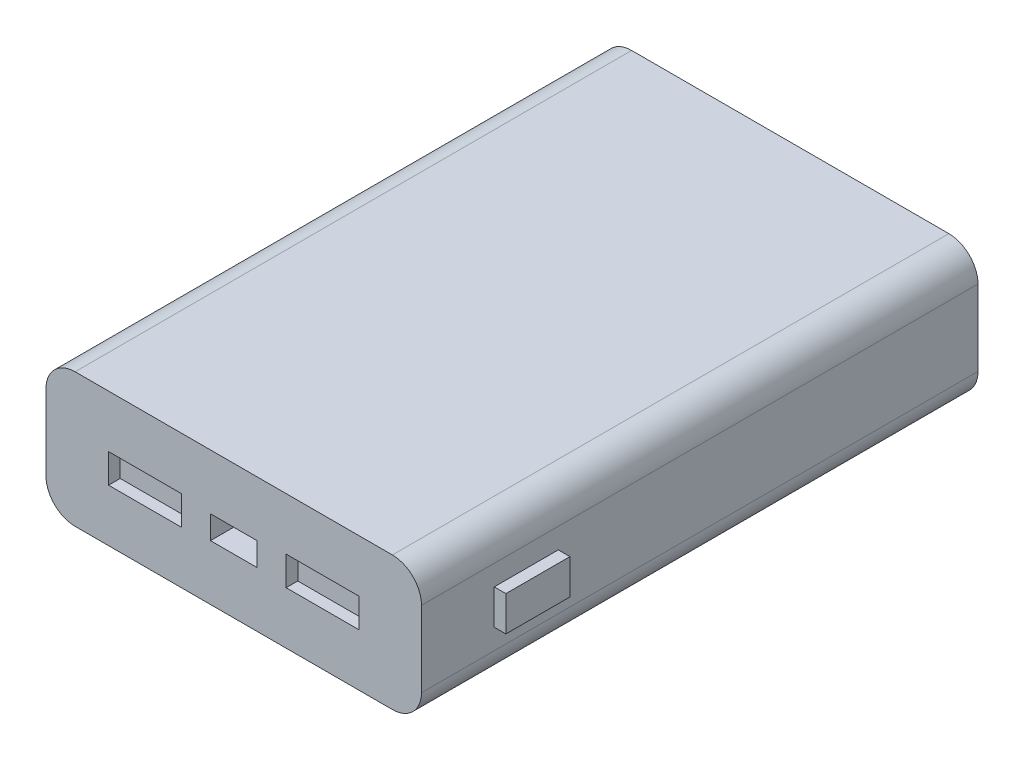
SolidWorks part; units mm, degrees
ref_plane "Front Plane" through (0, 0, 0) normal (0, 0, 1) x (1, 0, 0)
ref_plane "Top Plane" through (0, 0, 0) normal (0, 1, 0) x (1, 0, 0)
ref_plane "Right Plane" through (0, 0, 0) normal (1, 0, 0) x (0, 0, -1)
sketch "Sketch1" plane through (0, 0, 0) normal (0, 0, 1) x (1, 0, 0)
  line L1 (-32.25, -11.5) -> (32.25, -11.5)
  line L2 (-32.25, -11.5) -> (-32.25, 11.5)
  line L3 (-32.25, 11.5) -> (32.25, 11.5)
  line L4 (32.25, -11.5) -> (32.25, 11.5)
  line L5 (-32.25, -11.5) -> (32.25, 11.5) construction
  line L6 (-32.25, 11.5) -> (32.25, -11.5) construction
  point P0 (0, 0)
extrude "Boss-Extrude1" add sketch "Sketch1" along normal blind 95.6
fillet "Fillet1" radius 5 4 edges at (-32.25, -11.5, 47.8) (-32.25, 11.5, 47.8) (32.25, -11.5, 47.8) (32.25, 11.5, 47.8)
sketch "Sketch2" plane through (0, 0, 95.6) normal (0, 0, 1) x (1, 0, 0)
  line L1 (-4, -2) -> (4, -2)
  line L2 (-4, -2) -> (-4, 2)
  line L3 (-4, 2) -> (4, 2)
  line L4 (4, -2) -> (4, 2)
  line L5 (-4, -2) -> (4, 2) construction
  line L6 (-4, 2) -> (4, -2) construction
  point P0 (0, 0)
extrude "Cut-Extrude1" cut sketch "Sketch2" against normal blind 5
sketch "Sketch3" plane through (32.25, 0, 0) normal (1, 0, 0) x (0, 0, -1)
  line L0 (-95.6, 0) -> (-77.6, 0) construction
  line L5 (-95.6, -6.5) -> (-95.6, 6.5) construction
  line L7 (-83.1, -3) -> (-72.1, -3)
  line L8 (-83.1, -3) -> (-83.1, 3)
  line L9 (-83.1, 3) -> (-72.1, 3)
  line L10 (-72.1, -3) -> (-72.1, 3)
  line L11 (-83.1, -3) -> (-72.1, 3) construction
  line L12 (-83.1, 3) -> (-72.1, -3) construction
extrude "Boss-Extrude2" add sketch "Sketch3" along normal blind 2 separate body
sketch "Sketch4" plane through (0, 0, 95.6) normal (0, 0, 1) x (1, 0, 0)
  line L0 (-4, 2) -> (-4, -2) construction
  line L1 (-21.5, -2.5) -> (-9, -2.5)
  line L2 (-21.5, -2.5) -> (-21.5, 2.5)
  line L3 (-21.5, 2.5) -> (-9, 2.5)
  line L4 (-9, -2.5) -> (-9, 2.5)
  line L5 (-21.5, -2.5) -> (-9, 2.5) construction
  line L6 (-21.5, 2.5) -> (-9, -2.5) construction
  line L11 (0, 0) -> (0, 6.3343) construction
  line L12 (21.5, 2.5) -> (9, -2.5) construction
  line L13 (21.5, -2.5) -> (9, 2.5) construction
  line L14 (9, -2.5) -> (9, 2.5)
  line L15 (21.5, 2.5) -> (9, 2.5)
  line L16 (21.5, -2.5) -> (21.5, 2.5)
  line L17 (21.5, -2.5) -> (9, -2.5)
  point P0 (-15.25, 0)
  point P14 (15.25, 0)
  dimension "D1" = 5
extrude "Cut-Extrude2" cut sketch "Sketch4" against normal blind 2
sketch "Sketch5" plane through (0, -11.5, 0) normal (0, -1, 0) x (1, 0, 0)
  line L0 (-27.25, 95.6) -> (27.25, 95.6) construction
  line L1 (7.75, 73.1) -> (24.75, 73.1)
  line L2 (7.75, 73.1) -> (7.75, 86.1)
  line L3 (7.75, 86.1) -> (24.75, 86.1)
  line L4 (24.75, 73.1) -> (24.75, 86.1)
  line L5 (7.75, 73.1) -> (24.75, 86.1) construction
  line L6 (7.75, 86.1) -> (24.75, 73.1) construction
  line L7 (32.25, 95.6) -> (32.25, 0) construction
  point P0 (16.25, 79.6)
  dimension "D1" = 16
  dimension "D2" = 16
extrude "Cut-Extrude3" cut sketch "Sketch5" against normal blind 2
